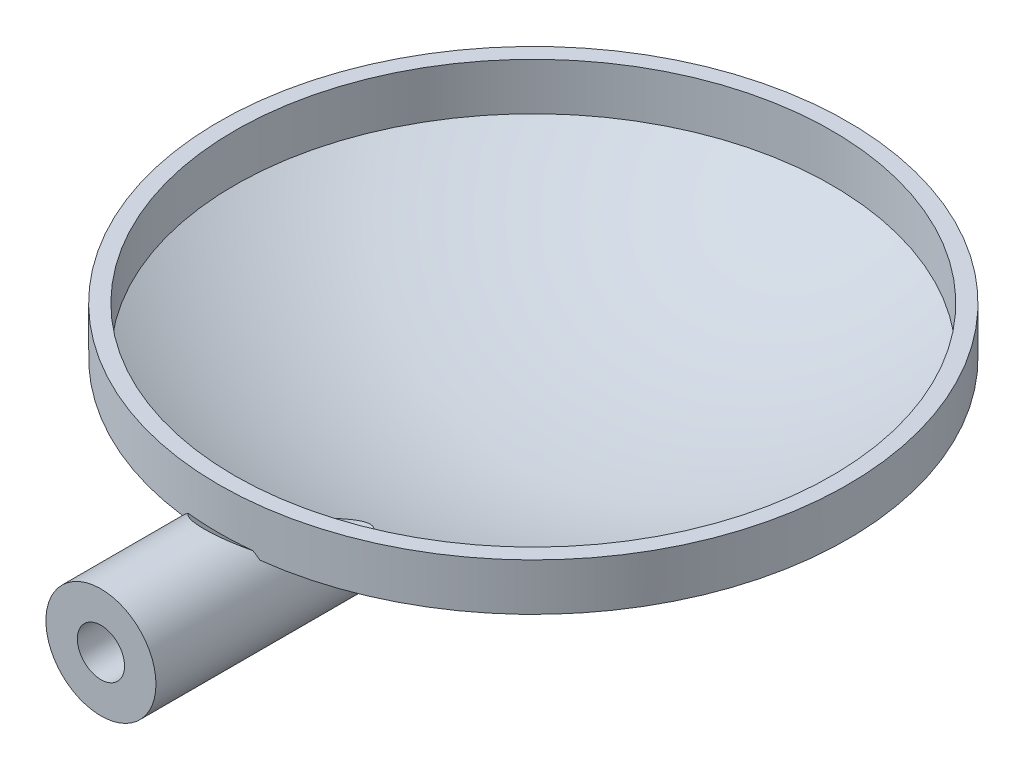
SolidWorks part; units mm, degrees
ref_plane "Płaszczyzna przednia" through (0, 0, 0) normal (0, 0, 1) x (1, 0, 0)
ref_plane "Płaszczyzna górna" through (0, 0, 0) normal (0, 1, 0) x (1, 0, 0)
ref_plane "Płaszczyzna prawa" through (0, 0, 0) normal (1, 0, 0) x (0, 0, -1)
sketch "Szkic1" plane through (0, 0, 0) normal (1, 0, 0) x (0, 0, -1)
  line L0 (0, 0) -> (0, -16.7798) construction
  line L1 (0, 0) -> (68.0197, 0) construction
  line L2 (0, -16.97) -> (0, -17.97)
  line L3 (38, 0) -> (40, 0)
  line L4 (40, 0) -> (40, -6)
  line L5 (40, -6) -> (39, -6)
  line L6 (68.0197, -6) -> (0, -6) construction
  line L7 (38, 0) -> (38, -6)
  line L8 (-6.7047, -17.97) -> (24.3698, -17.97) construction
  arc A0 (38, -6) -> (0, -16.97) centre (0.5649, 52.374) cw
  arc A2 (39, -6) -> (0, -17.97) centre (0, 51.5488) cw
  dimension "D7" = 1
  dimension "D1" = 1
  dimension "D2" = 17.97
  dimension "D3" = 2
  dimension "D4" = 6
  dimension "D5" = 1
  dimension "D6" = 40
revolve "Obrót1" add sketch "Szkic1" angle 360 about L0
ref_plane "Płaszczyzna1" through (0, 0, 55) normal (0, 0, 1) x (1, 0, 0)
sketch "Szkic2" plane through (0, 0, 55) normal (0, 0, 1) x (1, 0, 0)
  line L0 (0, 12.285) -> (0, -34.225) construction
  circle A0 centre (0, -10.97) radius 7
  arc A1 (-39, -6) -> (39, -6) centre (0, 51.5488) ccw construction
  dimension "D1" = 14
extrude "Dodanie-wyciągnięcie1" add sketch "Szkic2" against normal up to surface (25.4152 mm away)
sketch "Szkic3" plane through (0, 0, 55) normal (0, 0, 1) x (1, 0, 0)
  line L0 (0, 18.3337) -> (0, -40.6349) construction
  circle A0 centre (0, -10.97) radius 3
  dimension "D1" = 6
  dimension "D2" = 10.97
extrude "Wytnij-wyciągnięcie1" cut sketch "Szkic3" against normal up to surface (26.3705 mm away)
